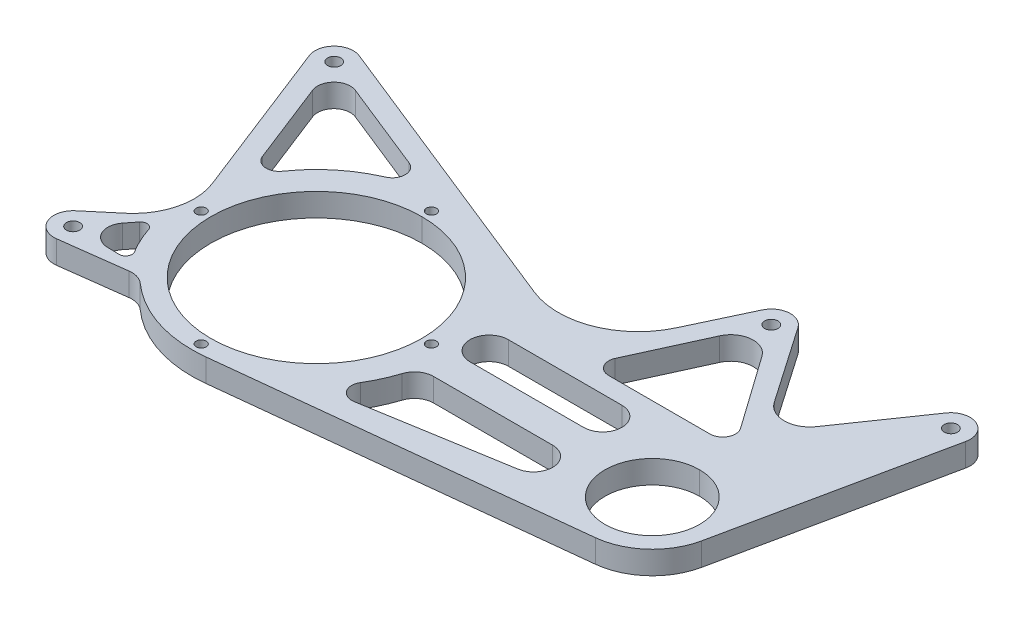
SolidWorks part; units mm, degrees
material "7075-T6 (SN)"
ref_plane "X-Y Datum" through (0, 0, 0) normal (0, 0, 1) x (1, 0, 0)
ref_plane "X-Z Datum" through (0, 0, 0) normal (0, 1, 0) x (1, 0, 0)
ref_plane "Y-Z Datum" through (0, 0, 0) normal (1, 0, 0) x (0, 0, -1)
sketch "Sketch1" plane through (0, 0, 0) normal (0, 1, 0) x (1, 0, 0)
  line L0 (-228.6, -165.1) -> (-123.19, -116.0015) construction
  line L1 (0, 0) -> (54.61, -127) construction
  line L2 (-123.19, -116.0015) -> (54.61, -127) construction
  line L3 (-228.6, -165.1) -> (-228.6, 0) construction
  line L4 (-116.84, 0) -> (0, 0) construction
  line L5 (-228.6, 0) -> (-116.84, 0) construction
  line L10 (-228.6, 0) -> (-123.19, -116.0015) construction
  line L11 (-123.19, -116.0015) -> (10.0337, -23.3342) construction
  line L15 (-207.9749, -9.9568) -> (-62.7807, -68.145)
  line L16 (-116.4944, -177.5509) -> (58.0437, -158.5638)
  line L17 (17.8716, -17.9218) -> (44.1595, -55.9906)
  line L18 (1.4126, -19.2843) -> (-12.1766, -48.2122)
  line L20 (-211.7072, -147.0868) -> (-198.1514, -135.6819)
  line L21 (-220.3888, -22.2676) -> (-189.4301, -101.4224)
  line L22 (-172.4434, -159.7008) -> (-204.3552, -163.8219)
  line L23 (54.61, -249.6025) -> (54.61, -4.3975) construction
  line L24 (109.22, 0) -> (54.61, -127) construction
  line L25 (108.5063, -25.2997) -> (85.6767, -133.5518)
  line L26 (91.3484, -17.9218) -> (65.0605, -55.9906)
  circle A0 centre (-211.5182, -18.7982) radius 9.525 construction
  circle A2 centre (10.0337, -23.3342) radius 9.525 construction
  circle A3 centre (-211.5182, -18.7982) radius 3.3 construction
  circle A4 centre (-205.5752, -154.3754) radius 3.3 construction
  circle A5 centre (-123.19, -116.0015) radius 52.3875
  circle A6 centre (54.61, -127) radius 23.5
  circle A7 centre (0, 0) radius 12.7 construction
  circle A8 centre (-228.6, -165.1) radius 12.7 construction
  circle A9 centre (-228.6, 0) radius 12.7 construction
  circle A10 centre (10.0337, -23.3342) radius 3.3 construction
  circle A11 centre (-123.19, -173.1515) radius 2.5 construction
  circle A14 centre (-123.19, -116.0015) radius 61.9125 construction
  circle A15 centre (-123.19, -116.0015) radius 57.15 construction
  circle A17 centre (-205.5752, -154.3754) radius 9.525 construction
  circle A18 centre (54.61, -127) radius 31.75 construction
  circle A19 centre (-48.0406, -31.3647) radius 39.624 construction
  arc A20 (-12.1766, -48.2122) -> (-62.7807, -68.145) centre (-48.0406, -31.3647) cw
  arc A24 (58.0437, -158.5638) -> (85.6767, -133.5518) centre (54.61, -127) ccw
  arc A25 (1.4126, -19.2843) -> (17.8716, -17.9218) centre (10.0337, -23.3342) cw
  circle A27 centre (-217.6792, -112.471) radius 30.3329 construction
  arc A29 (-198.1514, -135.6819) -> (-189.4301, -101.4224) centre (-217.6792, -112.471) ccw
  arc A30 (-220.3888, -22.2676) -> (-207.9749, -9.9568) centre (-211.5182, -18.7982) cw
  arc A31 (-164.4265, -162.1827) -> (-116.4944, -177.5509) centre (-123.19, -116.0015) ccw
  circle A32 centre (-171.1504, -169.7128) radius 10.0952 construction
  arc A33 (-204.3552, -163.8219) -> (-211.7072, -147.0868) centre (-205.5752, -154.3754) cw
  arc A34 (-172.4434, -159.7008) -> (-164.4265, -162.1827) centre (-171.1504, -169.7128) cw
  circle A35 centre (109.22, 0) radius 12.7 construction
  circle A36 centre (99.1863, -23.3342) radius 3.3 construction
  circle A37 centre (99.1863, -23.3342) radius 9.525 construction
  arc A38 (91.3484, -17.9218) -> (108.5063, -25.2997) centre (99.1863, -23.3342) cw
  arc A39 (44.1595, -55.9906) -> (65.0605, -55.9906) centre (54.61, -48.7741) ccw
  point P36 (-123.19, -116.0015)
  point P57 (54.61, -127)
  point P68 (54.61, -71.1243)
  dimension "D1" = 165.1
  dimension "D2" = 105.41
  dimension "D8" = 25.4
  dimension "D9" = 104.775
  dimension "D10" = 47
  dimension "D11" = 19.05
  dimension "D12" = 6.6
  dimension "D23" = 5
  dimension "D14" = 123.825
  dimension "D19" = 79.248
  dimension "D20" = 31.3647
  dimension "D16" = 63.5
  dimension "D25" = 20.1904
  dimension "D21" = 20.9
  dimension "D26" = 60.6657
  dimension "D28" = 12.7
  dimension "D3" = 111.76
  dimension "D4" = 228.6
  dimension "D5" = 127
  dimension "D6" = 49.0985
  dimension "D7" = 283.21
  dimension "D13" = 25.4
  dimension "D15" = 25.4
  dimension "D17" = 25.4
  dimension "D18" = 48.0406
  dimension "D22" = 34.4248
  dimension "D24" = 57.15
  dimension "D27" = 10.9208
  dimension "D29" = 109.22
extrude "Boss-Extrude1" add sketch "Sketch1" along normal mid plane 11.43
hole_wizard "M6 Clearance Hole1" positions "Sketch2" profile "Sketch3" hole size "M6" standard "ANSI Metric" end condition through all
sketch "Sketch2" plane through (0, -5.715, 0) normal (0, -1, 0) x (-1, 0, 0)
  point P0 (-10.0337, -23.3342)
  point P3 (211.5182, -18.7982)
  point P6 (205.5752, -154.3754)
  point P9 (-99.1863, -23.3342)
sketch "Sketch3" plane through (10.0337, -5.715, 23.3342) normal (1, 0, 0) x (0, 0, -1)
  line L0 (0, 0) -> (0, 11.43)
  line L1 (0, 11.43) -> (3.3, 11.43)
  line L2 (3.3, 11.43) -> (3.3, 0)
  line L5 (3.3, 0) -> (0, 0)
  line L11 (0, -6.35) -> (0, 107.95) construction
  dimension "Thru Hole Dia." = 6.6
  dimension "Thru Hole Depth" = 11.43
hole_wizard "Ø5.0mm Dowel Hole1" positions "Sketch4" profile "Sketch5" hole size "Ø5.0" standard "ANSI Metric" end condition through all
sketch "Sketch4" plane through (0, -5.715, 0) normal (0, -1, 0) x (-1, 0, 0)
  point P0 (123.19, -173.1515)
sketch "Sketch5" plane through (-123.19, -5.715, 173.1515) normal (1, 0, 0) x (0, 0, -1)
  line L0 (0, 0) -> (0, 11.43)
  line L1 (0, 11.43) -> (2.5, 11.43)
  line L2 (2.5, 11.43) -> (2.5, 0)
  line L5 (2.5, 0) -> (0, 0)
  line L11 (0, -6.35) -> (0, 107.95) construction
  dimension "Thru Hole Dia." = 5
  dimension "Thru Hole Depth" = 11.43
pattern_circular "CirPattern1" count 4 over 360 about axis through (-123.19, 0, 116.0015) along (0, 1, 0) of "Ø5.0mm Dowel Hole1"
ref_point "Point1"
ref_point "Point2"
ref_plane "Plane1" through (-123.19, 0, 0) normal (1, 0, 0) x (0, 0, -1)
ref_plane "Plane2" through (54.61, 0, 0) normal (1, 0, 0) x (0, 0, -1)
split line "Split Line1"
split line "Split Line2"
sketch "Sketch6" plane through (0, -5.715, 0) normal (0, -1, 0) x (1, 0, 0)
  line L0 (-14.2347, 76.5807) -> (2.0163, 40.925)
  line L1 (21.2013, 39.1139) -> (46.9848, 75.5459)
  line L2 (-204.6607, 36.3314) -> (-188.6269, 77.3262)
  line L3 (-194.0427, 25.8017) -> (-149.3861, 43.6983)
  line L5 (-8.4565, 85.5642) -> (41.8016, 85.5642)
  line L7 (85.6767, 133.5518) -> (108.5063, 25.2997) construction
  line L8 (-220.3888, 22.2676) -> (-189.4301, 101.4224) construction
  line L9 (17.8716, 17.9218) -> (44.1595, 55.9906) construction
  line L10 (1.4126, 19.2843) -> (-12.1766, 48.2122) construction
  line L11 (-207.9749, 9.9568) -> (-62.7807, 68.145) construction
  line L14 (91.3484, 17.9218) -> (65.0605, 55.9906) construction
  line L15 (-228.6, 165.1) -> (-123.19, 116.0015) construction
  line L16 (85.6767, 133.5518) -> (108.5063, 25.2997)
  line L17 (-190.9857, 136.0276) -> (-194.6927, 140.6895)
  line L18 (-182.1426, 155.013) -> (-188.0965, 154.851)
  line L19 (91.3484, 17.9218) -> (65.0605, 55.9906)
  line L20 (88.8993, 35.4374) -> (62.4646, 73.7187)
  line L21 (87.8783, 84.6466) -> (97.4783, 39.1264)
  line L22 (77.91, 131.9138) -> (100.7396, 23.6618) construction
  line L23 (97.88, 22.4321) -> (71.592, 60.5009) construction
  line L24 (65.1814, 83.1605) -> (79.1566, 89.1698)
  line L25 (109.22, 0) -> (54.61, 127) construction
  circle A0 centre (10.0337, 23.3342) radius 3.3 construction
  circle A1 centre (10.0337, 23.3342) radius 3.3 construction
  arc A2 (54.61, 103.5) -> (54.61, 150.5) centre (54.61, 127) ccw construction
  circle A3 centre (-8.4565, 79.2142) radius 6.35 construction
  circle A4 centre (41.8016, 79.2142) radius 6.35 construction
  circle A5 centre (12.1294, 45.5343) radius 11.114 construction
  arc A6 (2.0163, 40.925) -> (21.2013, 39.1139) centre (12.1294, 45.5343) ccw
  arc A8 (46.9848, 75.5459) -> (41.8016, 85.5642) centre (41.8016, 79.2142) ccw
  arc A9 (-14.2347, 76.5807) -> (-8.4565, 85.5642) centre (-8.4565, 79.2142) cw
  circle A10 centre (-182.5949, 74.967) radius 6.477 construction
  circle A11 centre (-151.7955, 49.7105) radius 6.477 construction
  circle A14 centre (-197.0734, 33.3639) radius 8.1469 construction
  arc A15 (-204.6607, 36.3314) -> (-194.0427, 25.8017) centre (-197.0734, 33.3639) ccw
  arc A20 (97.4783, 39.1264) -> (88.8993, 35.4374) centre (92.8183, 38.1436) cw
  arc A24 (79.1566, 89.1698) -> (87.8783, 84.6466) centre (81.665, 83.3363) cw
  arc A25 (-149.3861, 43.6983) -> (-149.2293, 55.6575) centre (-151.7955, 49.7105) ccw
  circle A26 centre (-123.19, 116.0015) radius 65.7225
  circle A27 centre (-123.19, 116.0015) radius 65.7225 construction
  arc A28 (-149.2293, 55.6575) -> (-177.2657, 78.6482) centre (-123.19, 116.0015) cw
  arc A29 (-188.6269, 77.3262) -> (-177.2657, 78.6482) centre (-182.5949, 74.967) cw
  circle A31 centre (-182.0558, 151.8264) radius 3.1877 construction
  circle A32 centre (-188.4906, 138.0115) radius 3.1877 construction
  circle A33 centre (-187.859, 146.1234) radius 8.7308 construction
  arc A34 (-185.4699, 136.9934) -> (-179.3328, 150.1692) centre (-123.19, 116.0015) cw
  arc A35 (-179.3328, 150.1692) -> (-182.1426, 155.013) centre (-182.0558, 151.8264) ccw
  arc A36 (-185.4699, 136.9934) -> (-190.9857, 136.0276) centre (-188.4906, 138.0115) cw
  arc A37 (-194.6927, 140.6895) -> (-188.0965, 154.851) centre (-187.859, 146.1234) cw
  arc A38 (62.4646, 73.7187) -> (65.1814, 83.1605) centre (67.6898, 77.3269) cw
  circle A39 centre (54.61, 127) radius 31.75 construction
  point P86 (72.169, 86.1652)
  point P88 (67.1521, 97.8323)
  dimension "D3" = 12.7
  dimension "D4" = 22.2001
  dimension "D5" = 12.954
  dimension "D9" = 6.3754
  dimension "D10" = 7.62
  dimension "D12" = 7.9375
  dimension "D13" = 4.7625
  dimension "D14" = 6.35
  dimension "D1" = 0.661
  dimension "D2" = 0.66
  dimension "D6" = 55.88
  dimension "D7" = 14.4448
  dimension "D8" = 3.81
  dimension "D11" = 7.62
  dimension "D15" = 12.7
extrude "Cut-Extrude1" cut sketch "Sketch6" against normal through all contours A9 L0 A6 L1 A8 L5 | A29 L2 A15 L3 A25 A28 | A37 L17 A36 A34 A35 L18
sketch "Sketch7" plane through (0, -5.715, 0) normal (0, -1, 0) x (1, 0, 0)
  line L0 (-48.8157, 114.0965) -> (7.5723, 114.0965)
  line L1 (-48.8157, 95.0465) -> (7.5723, 95.0465)
  line L4 (-60.4801, 159.9806) -> (9.1433, 148.338)
  line L6 (-51.5252, 129.4185) -> (7.5723, 129.4185)
  line L7 (-123.19, 116.0015) -> (54.61, 127) construction
  circle A0 centre (-48.8157, 104.5715) radius 9.525 construction
  circle A3 centre (7.5723, 104.5715) radius 9.525 construction
  arc A4 (-48.8157, 95.0465) -> (-48.8157, 114.0965) centre (-48.8157, 104.5715) cw
  arc A5 (7.5723, 95.0465) -> (7.5723, 114.0965) centre (7.5723, 104.5715) ccw
  circle A12 centre (-51.5252, 138.9435) radius 9.525 construction
  circle A13 centre (7.5723, 138.9435) radius 9.525 construction
  circle A14 centre (-61.5483, 153.5923) radius 6.477 construction
  arc A15 (-60.5967, 136.0394) -> (-67.0782, 150.2201) centre (-123.19, 116.0015) ccw
  arc A16 (-67.0782, 150.2201) -> (-60.4801, 159.9806) centre (-61.5483, 153.5923) cw
  arc A17 (-60.5967, 136.0394) -> (-51.5252, 129.4185) centre (-51.5252, 138.9435) ccw
  arc A18 (7.5723, 129.4185) -> (9.1433, 148.338) centre (7.5723, 138.9435) ccw
  circle A28 centre (-123.19, 116.0015) radius 65.7225
  circle A29 centre (-123.19, 116.0015) radius 65.7225 construction
  dimension "D1" = 19.05
  dimension "D2" = 11.43
  dimension "D5" = 12.954
  dimension "D3" = 14.8249
  dimension "D4" = 56.388
  dimension "D7" = 33.7133
  dimension "D6" = 3.81
extrude "Cut-Extrude2" cut sketch "Sketch7" against normal through all
